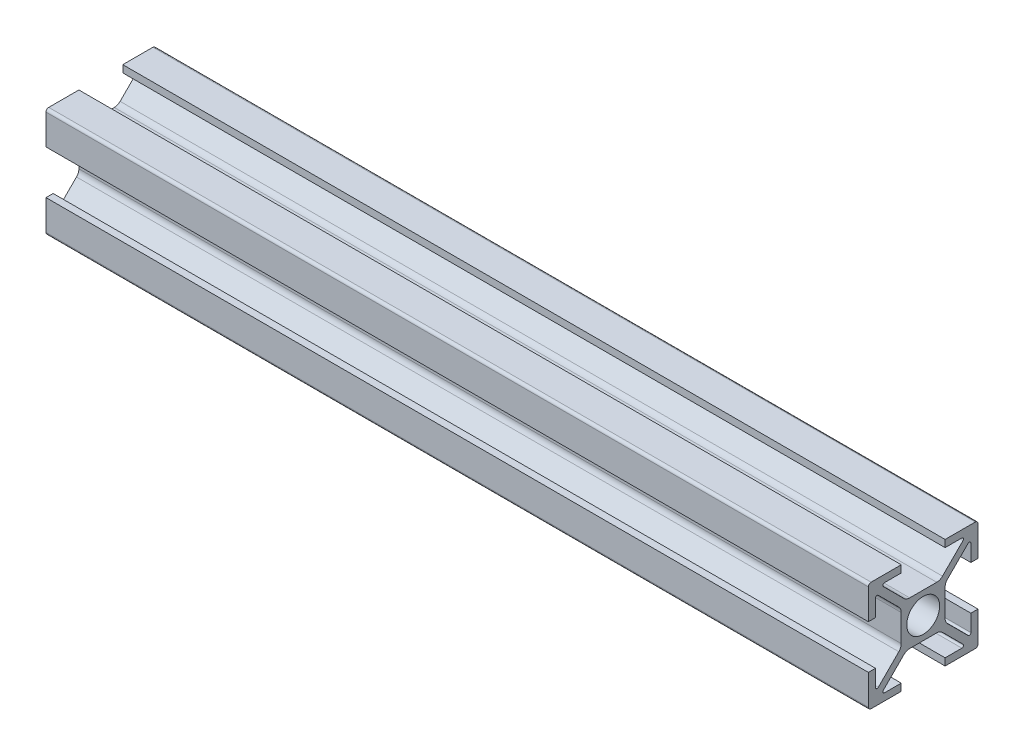
SolidWorks part; units mm, degrees
material "6063-T5"
ref_plane "Plano frontal" through (0, 0, 0) normal (0, 0, 1) x (1, 0, 0)
ref_plane "Plano superior" through (0, 0, 0) normal (0, 1, 0) x (1, 0, 0)
ref_plane "Plano direito" through (0, 0, 0) normal (1, 0, 0) x (0, 0, -1)
sketch "Esboço1" plane through (0, 0, 0) normal (0, 0, 1) x (1, 0, 0)
  line L0 (0, 0) -> (150, 0)
  dimension "D1" = 150
other "Quadrado PF20-01 - PERFIL 2020 BÁSICO(1)"
ref_plane "Plano1" through (0, 0, 0) normal (1, 0, 0) x (0, 1, 0)
sketch "Sketch1" plane through (0, 0, 0) normal (1, 0, 0) x (0, 1, 0)
  line L0 (8.1879, -7.2686) -> (4.4393, -3.5201)
  line L1 (4, -2.4594) -> (4, 2.4594)
  line L2 (4.4393, 3.5201) -> (8.1879, 7.2686)
  line L3 (8.7, 7.0565) -> (8.7, 4)
  line L4 (8.7, 4) -> (10, 4)
  line L5 (10, 4) -> (10, 9.5)
  line L6 (9.5, 10) -> (4, 10)
  line L7 (4, 10) -> (4, 8.7)
  line L8 (4, 8.7) -> (7.0565, 8.7)
  line L9 (7.2686, 8.1879) -> (3.5201, 4.4393)
  line L10 (2.4594, 4) -> (-2.4594, 4)
  line L11 (-3.5201, 4.4393) -> (-7.2686, 8.1879)
  line L12 (-7.0565, 8.7) -> (-4, 8.7)
  line L13 (-4, 8.7) -> (-4, 10)
  line L14 (-4, 10) -> (-9.5, 10)
  line L15 (-10, 9.5) -> (-10, 4)
  line L16 (-10, 4) -> (-8.7, 4)
  line L17 (-8.7, 4) -> (-8.7, 7.0565)
  line L18 (-8.1879, 7.2686) -> (-4.4393, 3.5201)
  line L19 (-4, 2.4594) -> (-4, -2.4594)
  line L20 (-4.4393, -3.5201) -> (-8.1879, -7.2686)
  line L21 (-8.7, -7.0565) -> (-8.7, -4)
  line L22 (-8.7, -4) -> (-10, -4)
  line L23 (-10, -4) -> (-10, -9.5)
  line L24 (-9.5, -10) -> (-4, -10)
  line L25 (-4, -10) -> (-4, -8.7)
  line L26 (-4, -8.7) -> (-7.0565, -8.7)
  line L27 (-7.2686, -8.1879) -> (-3.5201, -4.4393)
  line L28 (-2.4594, -4) -> (2.4594, -4)
  line L29 (3.5201, -4.4393) -> (7.2686, -8.1879)
  line L30 (7.0565, -8.7) -> (4, -8.7)
  line L31 (4, -8.7) -> (4, -10)
  line L32 (4, -10) -> (9.5, -10)
  line L33 (10, -9.5) -> (10, -4)
  line L34 (10, -4) -> (8.7, -4)
  line L35 (8.7, -4) -> (8.7, -7.0565)
  circle A0 centre (0, 0) radius 3
  arc A1 (8.1879, -7.2686) -> (8.7, -7.0565) centre (8.4, -7.0565) ccw
  arc A2 (4, -2.4594) -> (4.4393, -3.5201) centre (5.5, -2.4594) ccw
  arc A3 (4.4393, 3.5201) -> (4, 2.4594) centre (5.5, 2.4594) ccw
  arc A4 (8.7, 7.0565) -> (8.1879, 7.2686) centre (8.4, 7.0565) ccw
  arc A5 (10, 9.5) -> (9.5, 10) centre (9.5, 9.5) ccw
  arc A6 (7.2686, 8.1879) -> (7.0565, 8.7) centre (7.0565, 8.4) ccw
  arc A7 (2.4594, 4) -> (3.5201, 4.4393) centre (2.4594, 5.5) ccw
  arc A8 (-3.5201, 4.4393) -> (-2.4594, 4) centre (-2.4594, 5.5) ccw
  arc A9 (-7.0565, 8.7) -> (-7.2686, 8.1879) centre (-7.0565, 8.4) ccw
  arc A10 (-9.5, 10) -> (-10, 9.5) centre (-9.5, 9.5) ccw
  arc A11 (-8.1879, 7.2686) -> (-8.7, 7.0565) centre (-8.4, 7.0565) ccw
  arc A12 (-4, 2.4594) -> (-4.4393, 3.5201) centre (-5.5, 2.4594) ccw
  arc A13 (-4.4393, -3.5201) -> (-4, -2.4594) centre (-5.5, -2.4594) ccw
  arc A14 (-8.7, -7.0565) -> (-8.1879, -7.2686) centre (-8.4, -7.0565) ccw
  arc A15 (-10, -9.5) -> (-9.5, -10) centre (-9.5, -9.5) ccw
  arc A16 (-7.2686, -8.1879) -> (-7.0565, -8.7) centre (-7.0565, -8.4) ccw
  arc A17 (-2.4594, -4) -> (-3.5201, -4.4393) centre (-2.4594, -5.5) ccw
  arc A18 (3.5201, -4.4393) -> (2.4594, -4) centre (2.4594, -5.5) ccw
  arc A19 (7.0565, -8.7) -> (7.2686, -8.1879) centre (7.0565, -8.4) ccw
  arc A20 (9.5, -10) -> (10, -9.5) centre (9.5, -9.5) ccw
  point P0 (0, 10)
  point P1 (-10, 10)
  point P2 (10, 10)
  point P3 (10, 0)
  point P4 (10, -10)
  point P5 (0, -10)
  point P6 (-10, -10)
  point P7 (-10, 0)
  point P8 (0, 0)
  point P87 (0, 0)
